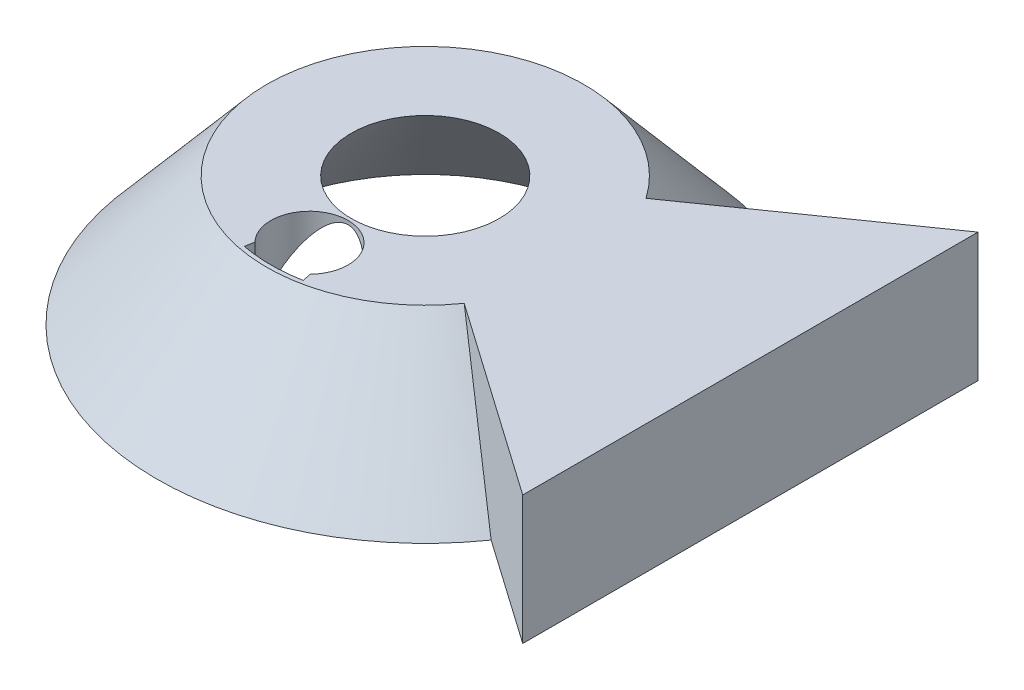
SolidWorks part; units mm, degrees
ref_plane "Front Plane" through (0, 0, 0) normal (0, 0, 1) x (1, 0, 0)
ref_plane "Top Plane" through (0, 0, 0) normal (0, 1, 0) x (1, 0, 0)
ref_plane "Right Plane" through (0, 0, 0) normal (1, 0, 0) x (0, 0, -1)
sketch "Sketch1" plane through (0, 0, 0) normal (1, 0, 0) x (0, 0, -1)
  line L0 (11.5, 20) -> (28.55, 0)
  line L1 (0, 0) -> (0, 53.3807) construction
  line L2 (55, 0) -> (-55, 0) construction
  line L3 (28.55, 0) -> (41.6906, 0)
  line L4 (41.6906, 0) -> (24.6406, 20)
  line L5 (24.6406, 20) -> (11.5, 20)
  line L6 (0, 55) -> (0, -55) construction
  dimension "D1" = 11.5
  dimension "D2" = 28.55
  dimension "D3" = 20
  dimension "D4" = 10
revolve "Revolve1" add sketch "Sketch1" angle 360 about L1
sketch "Sketch3" plane through (0, 0, 0) normal (0, 0, 1) x (1, 0, 0)
  line L0 (24.6406, 20) -> (61.6906, 20)
  line L1 (41.6906, 0) -> (61.6906, 0)
  line L2 (55, 0) -> (-55, 0) construction
  line L3 (41.6906, 0) -> (24.6406, 20)
  line L4 (-41.6906, 0) -> (41.6906, 0) construction
  line L5 (0, 0) -> (0, 31.2835) construction
  line L6 (61.6906, 0) -> (61.6906, 20)
  dimension "D1" = 20
revolve "Revolve2" add sketch "Sketch3" angle 70 mid plane about L5
sketch "Sketch4" plane through (0, 0, 0) normal (0, 0, 1) x (1, 0, 0)
  line L0 (50.534, 0) -> (50.534, 20) construction
  line L1 (50.534, 46.1291) -> (105.2141, 46.1291)
  line L2 (50.534, 46.1291) -> (50.534, -20.5906)
  line L3 (50.534, -20.5906) -> (105.2141, -20.5906)
  line L4 (105.2141, 46.1291) -> (105.2141, -20.5906)
extrude "Cut-Extrude1" cut sketch "Sketch4" against normal through all both and the other way through all
sketch "Sketch5" plane through (0, 0, 0) normal (0, 1, 0) x (1, 0, 0)
  line L0 (0, -11.4668) -> (0, 11.4668) construction
  line L1 (-11.4668, 0) -> (11.4668, 0) construction
  circle A0 centre (0, -18) radius 6
  dimension "D1" = 12
  dimension "D2" = 18
extrude "Cut-Extrude2" cut sketch "Sketch5" along normal blind 40
sketch "Sketch7" plane through (0, 0, 0) normal (1, 0, 0) x (0, 0, -1)
  line L0 (-43.7361, -8.5629) -> (-24, 14.946)
  line L1 (-24, 14.946) -> (-24, 20)
  line L2 (-24, 20) -> (-18.4316, 20)
  line L3 (-18.7049, 12.5637) -> (-17.3882, -8.5629)
  line L4 (-17.3882, -8.5629) -> (-43.7361, -8.5629)
  line L5 (-18.4316, 20) -> (-18.7049, 12.5637)
  line L6 (0, 0) -> (0, 21.7475) construction
revolve "Cut-Revolve1" cut sketch "Sketch7" angle 22 mid plane about L6
